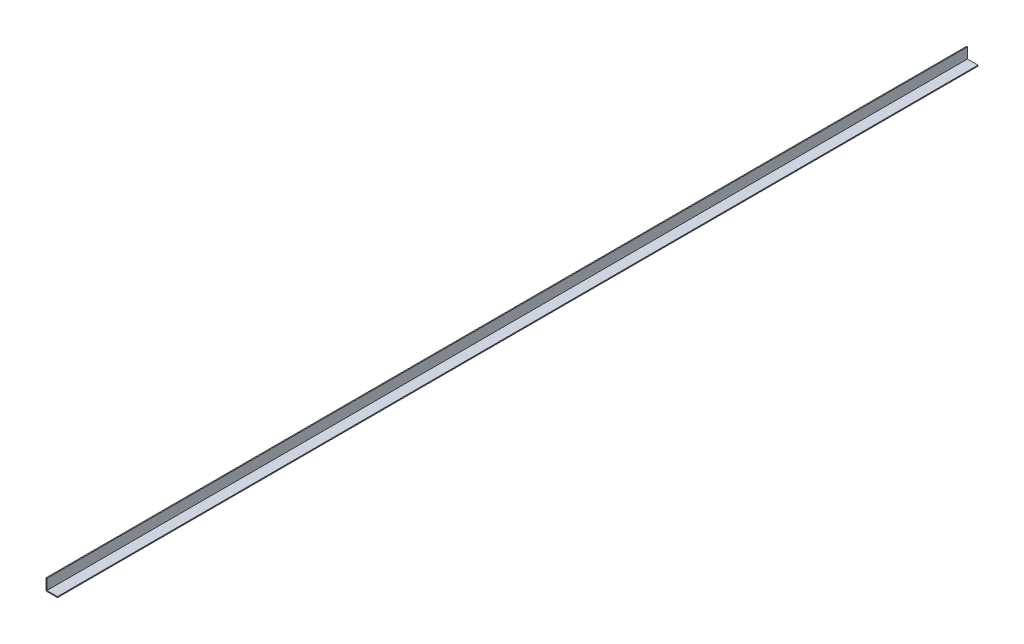
SolidWorks part; units mm, degrees
material "ASTM A36 Acero"
ref_plane "Alzado" through (0, 0, 0) normal (0, 0, 1) x (1, 0, 0)
ref_plane "Planta" through (0, 0, 0) normal (0, 1, 0) x (1, 0, 0)
ref_plane "Vista lateral" through (0, 0, 0) normal (1, 0, 0) x (0, 0, -1)
sketch "Croquis1" plane through (0, 0, 0) normal (0, 0, 1) x (1, 0, 0)
  line L0 (0, 76.2) -> (0, 0)
  line L1 (0, 0) -> (76.2, 0)
  line L2 (76.2, 0) -> (76.2, 6.35)
  line L3 (76.2, 6.35) -> (6.35, 6.35)
  line L4 (6.35, 6.35) -> (6.35, 76.2)
  line L5 (6.35, 76.2) -> (0, 76.2)
  dimension "D1" = 6.35
  dimension "D2" = 76.2
extrude "Saliente-Extruir1" add sketch "Croquis1" against normal blind 6100
